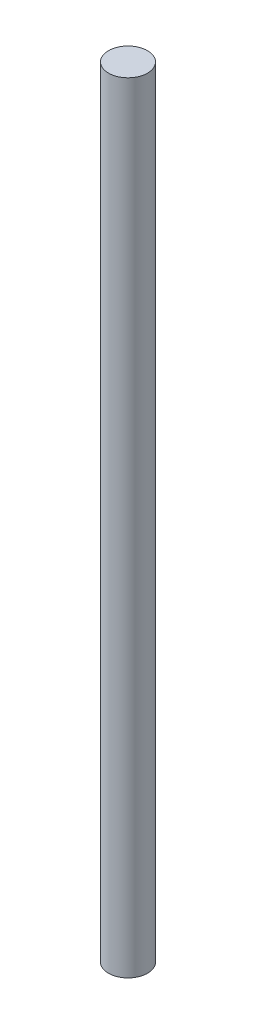
SolidWorks part; units mm, degrees
ref_plane "Front Plane" through (0, 0, 0) normal (0, 0, 1) x (1, 0, 0)
ref_plane "Top Plane" through (0, 0, 0) normal (0, 1, 0) x (1, 0, 0)
ref_plane "Right Plane" through (0, 0, 0) normal (1, 0, 0) x (0, 0, -1)
sketch "Sketch1" plane through (0, 0, 0) normal (0, 1, 0) x (1, 0, 0)
  circle A0 centre (0, 0) radius 7.62
  dimension "D1" = 15.24
extrude "Boss-Extrude1" add sketch "Sketch1" along normal blind 304.8
